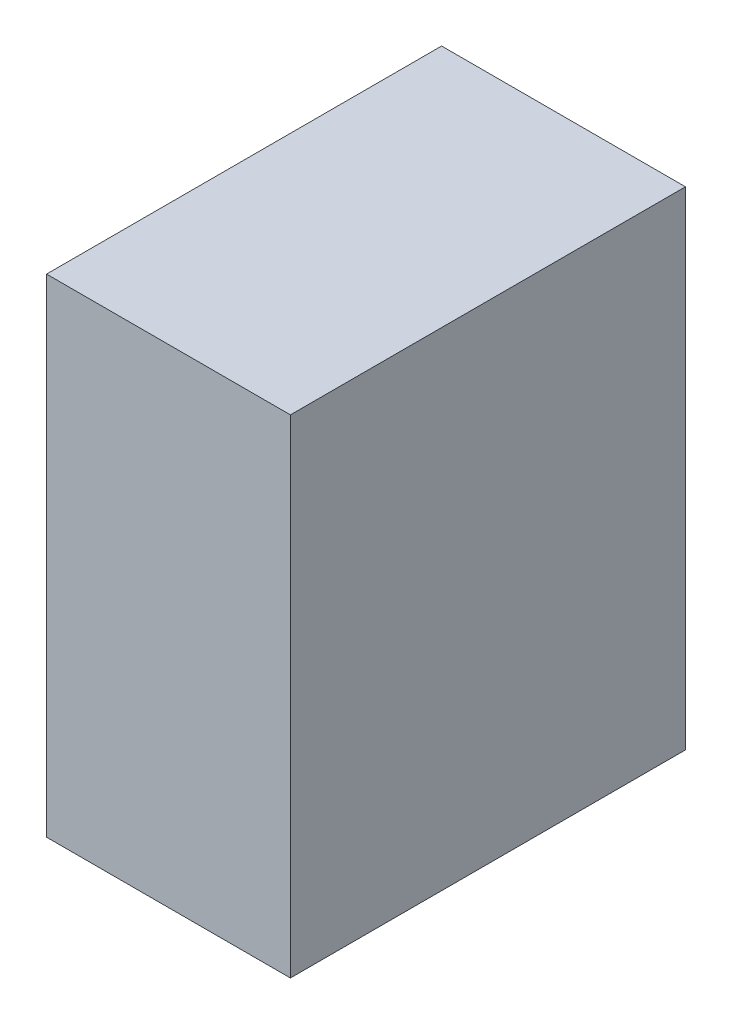
SolidWorks part; units mm, degrees
ref_plane "Front Plane" through (0, 0, 0) normal (0, 0, 1) x (1, 0, 0)
ref_plane "Top Plane" through (0, 0, 0) normal (0, 1, 0) x (1, 0, 0)
ref_plane "Right Plane" through (0, 0, 0) normal (1, 0, 0) x (0, 0, -1)
sketch "Sketch1" plane through (0, 0, 0) normal (1, 0, 0) x (0, 0, -1)
  line L1 (0, 0) -> (16.2, 0)
  line L2 (0, 0) -> (0, 20)
  line L3 (0, 20) -> (16.2, 20)
  line L4 (16.2, 0) -> (16.2, 20)
extrude "Boss-Extrude1" add sketch "Sketch1" against normal blind 10
